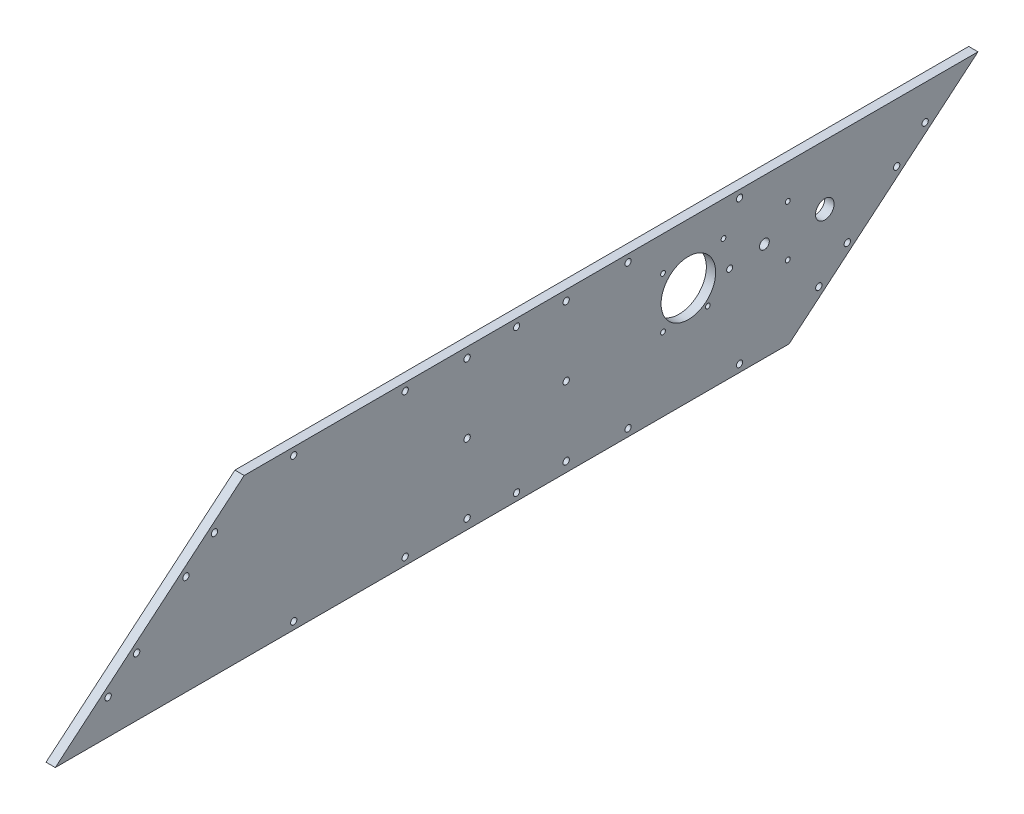
SolidWorks part; units mm, degrees
material "6061-T6 (SS)"
ref_plane "Front Plane" through (0, 0, 0) normal (0, 0, 1) x (1, 0, 0)
ref_plane "Top Plane" through (0, 0, 0) normal (0, 1, 0) x (1, 0, 0)
ref_plane "Right Plane" through (0, 0, 0) normal (1, 0, 0) x (0, 0, -1)
sketch "Sketch1" plane through (0, 0, 0) normal (1, 0, 0) x (0, 0, -1)
  line L0 (0, 12.7) -> (0, -12.7) construction
  line L1 (0, -12.7) -> (33.2976, -40.64) construction
  line L2 (33.2976, -40.64) -> (312.6976, -40.64)
  line L3 (312.6976, -40.64) -> (345.9952, -12.7)
  line L4 (345.9952, -12.7) -> (345.9952, 12.7) construction
  line L5 (345.9952, 12.7) -> (312.6976, 40.64) construction
  line L6 (312.6976, 40.64) -> (33.2976, 40.64)
  line L7 (33.2976, 40.64) -> (0, 12.7)
  line L8 (33.2976, 40.64) -> (33.2976, -40.64) construction
  line L9 (312.6976, 40.64) -> (312.6976, -40.64) construction
  line L10 (0, 0) -> (345.9952, 0) construction
  line L11 (0, 12.7) -> (-63.5681, -40.64)
  line L12 (-63.5681, -40.64) -> (33.2976, -40.64)
  line L13 (312.6976, 40.64) -> (409.5633, 40.64)
  line L14 (409.5633, 40.64) -> (345.9952, -12.7)
  point P10 (33.2976, 0)
  point P12 (312.6976, 0)
  dimension "D1" = 81.28
  dimension "D2" = 279.4
  dimension "D3" = 25.4
  dimension "D4" = 40
extrude "Boss-Extrude1" add sketch "Sketch1" along normal blind 4.7625
sketch "Sketch2" plane through (4.7625, 0, 0) normal (1, 0, 0) x (0, 0, -1)
  line L0 (-3.2177, 10) -> (373.048, 10) construction
  line L1 (312.6976, -40.64) -> (409.5633, 40.64) construction
  line L2 (345.048, 10) -> (245.048, 10) construction
  line L3 (245.048, -5) -> (345.048, -5) construction
  line L4 (245.048, -5) -> (245.048, 25) construction
  line L5 (245.048, 25) -> (345.048, 25) construction
  line L6 (345.048, -5) -> (345.048, 25) construction
  line L7 (33.2976, 40.64) -> (-63.5681, -40.64) construction
  line L9 (0, 0) -> (361.1305, 0) construction
  circle A0 centre (300.048, 10) radius 2.5
  circle A1 centre (282.2147, 8) radius 1.51
  circle A2 centre (270.2178, 15.9334) radius 1.01 construction
  circle A3 centre (282.2147, 8) radius 11.4777 construction
  circle A4 centre (270.2178, 15.9334) radius 7.1501 construction
  circle A5 centre (300.048, 10) radius 12.827 construction
  circle A6 centre (261.048, 10) radius 14
  circle A7 centre (282.2147, 8) radius 5.1181 construction
  circle A8 centre (331.0042, 10) radius 4.7625
  point P11 (300.048, 10)
  point P12 (282.2147, 8)
  point P13 (270.2178, 15.9334)
  point P23 (261.048, 10)
  dimension "D5" = 5
  dimension "D6" = 3.02
  dimension "D7" = 2.02
  dimension "D8" = 25.654
  dimension "D9" = 22.9553
  dimension "D10" = 14.3002
  dimension "D12" = 28
  dimension "D13" = 10.2362
  dimension "D17" = 9.525
  dimension "D1" = 17.9451
  dimension "D2" = 14.3828
  dimension "D3" = 30
  dimension "D4" = 100
  dimension "D11" = 10.922
  dimension "D14" = 16
  dimension "D15" = 13
  dimension "D16" = 55
  dimension "D18" = 30.9562
  dimension "D19" = 28
  dimension "D20" = 10
extrude "Gearbox (with Slip fits)" cut sketch "Sketch2" against normal through all
hole_wizard "#4-40 Tapped Hole1" [suppressed] positions "Sketch4" profile "Sketch3" tap size "#4-40" standard "ANSI Inch"
sketch "Sketch4" plane through (0, 40.64, 0) normal (0, 1, 0) x (1, 0, 0)
  line L0 (2.3812, 312.6976) -> (2.3813, 33.2976) construction
  line L1 (4.7625, 312.6976) -> (0, 312.6976) construction
  line L2 (4.7625, 33.2976) -> (0, 33.2976) construction
  point P9 (2.3812, 306.3476)
  point P33 (2.3813, 260.1196)
  point P34 (2.3813, 213.8916)
  point P35 (2.3813, 167.6636)
  point P36 (2.3813, 121.4356)
  point P37 (2.3813, 75.2076)
  point P38 (2.3813, 28.9796)
  dimension "D1" = 6.35
sketch "Sketch3" plane through (2.3812, 40.64, -306.3476) normal (1, 0, 0) x (0, 0, 1)
  line L0 (0, 0) -> (0, 8.2992)
  line L1 (0, 8.2992) -> (1.1303, 7.62)
  line L2 (1.1303, 7.62) -> (1.1303, 0)
  line L5 (1.1303, 0) -> (0, 0)
  line L10 (0, 8.2992) -> (-1.1303, 7.62) construction
  line L11 (0, -6.35) -> (0, 107.95) construction
  dimension "Tap Drill Dia." = 2.2606
  dimension "Tap Drill Depth" = 7.62
  dimension "Drill Angle" = 118
cosmetic thread "Hole Thread1" [suppressed] parameters "D1"=5.588, "D2"=2.8448
cosmetic thread "Hole Thread2" [suppressed] parameters "D1"=5.588, "D2"=2.8448
cosmetic thread "Hole Thread3" [suppressed] parameters "D1"=5.588, "D2"=2.8448
cosmetic thread "Hole Thread4" [suppressed] parameters "D1"=5.588, "D2"=2.8448
cosmetic thread "Hole Thread5" [suppressed] parameters "D1"=5.588, "D2"=2.8448
cosmetic thread "Hole Thread6" [suppressed] parameters "D1"=5.588, "D2"=2.8448
cosmetic thread "Hole Thread7" [suppressed] parameters "D1"=5.588, "D2"=2.8448
sketch "Sketch5" plane through (4.7625, 0, 0) normal (1, 0, 0) x (0, 0, -1)
  line L0 (0, 0) -> (361.1305, 0) construction
  line L1 (28.757, 36.83) -> (405.0227, 36.83) construction
  line L4 (33.2976, 40.64) -> (-63.5681, -40.64) construction
  line L5 (409.5633, 40.64) -> (33.2976, 40.64) construction
  line L6 (312.6976, -40.64) -> (409.5633, 40.64) construction
  circle A0 centre (287.2976, 36.83) radius 1.5939
  circle A1 centre (230.1476, 36.83) radius 1.5939
  circle A2 centre (172.9976, 36.83) radius 1.5939
  circle A3 centre (115.8476, 36.83) radius 1.5938
  circle A4 centre (58.6976, 36.83) radius 1.5938
  circle A5 centre (58.6976, -36.83) radius 1.5938
  circle A6 centre (115.8476, -36.83) radius 1.5938
  circle A7 centre (172.9976, -36.83) radius 1.5939
  circle A8 centre (230.1476, -36.83) radius 1.5939
  circle A9 centre (287.2976, -36.83) radius 1.5939
  dimension "D1" = 3.1877
  dimension "D3" = 25.4
  dimension "D4" = 3.81
  dimension "D2" = 5
extrude "Cut-Extrude1" cut sketch "Sketch5" against normal through all
hole_wizard "#2 Clearance Hole1" positions "Sketch8" profile "Sketch7" hole size "#2" standard "ANSI Inch" end condition through all
sketch "Sketch8" plane through (4.7625, 0, 0) normal (1, 0, 0) x (0, 0, -1)
  line L0 (245.048, 40.64) -> (245.048, -40.64) construction
  line L1 (409.5633, 40.64) -> (33.2976, 40.64) construction
  line L2 (-63.5681, -40.64) -> (312.6976, -40.64) construction
  line L4 (245.048, -6) -> (291.9785, -6) construction
  line L7 (248.048, -6) -> (248.048, 23) construction
  line L8 (245.048, -3) -> (312.048, -3) construction
  line L10 (245.048, 23) -> (312.048, 23) construction
  line L11 (312.048, 23) -> (312.048, -3) construction
  circle A0 centre (261.048, 10) radius 14 construction
  point P17 (248.048, 23)
  point P19 (279.048, 23)
  point P21 (271.048, -3)
  point P31 (248.048, -3)
  point P41 (312.048, 23)
  point P43 (312.048, -3)
  dimension "D1" = 16
  dimension "D2" = 16
  dimension "D3" = 34
  dimension "D4" = 26
  dimension "D5" = 3
  dimension "D6" = 3
  dimension "D7" = 29
  dimension "D8" = 67
sketch "Sketch7" plane through (4.7625, 23, -248.048) normal (0, 1, 0) x (0, 0, -1)
  line L0 (0, 0) -> (0, 4.7625)
  line L1 (0, 4.7625) -> (1.2192, 4.7625)
  line L2 (1.2192, 4.7625) -> (1.2192, 0)
  line L5 (1.2192, 0) -> (0, 0)
  line L11 (0, -6.35) -> (0, 107.95) construction
  dimension "Thru Hole Dia." = 2.4384
  dimension "Thru Hole Depth" = 4.7625
hole_wizard "#4 Clearance Hole2" positions "Sketch10" profile "Sketch9" hole size "#4" standard "ANSI Inch" end condition through all
sketch "Sketch10" plane through (4.7625, 0, 0) normal (1, 0, 0) x (0, 0, -1)
  line L0 (-15.1353, 0) -> (361.1305, 0) construction
  line L1 (33.2976, 40.64) -> (-63.5681, -40.64) construction
  line L2 (312.6976, -40.64) -> (409.5633, 40.64) construction
  line L4 (27.2435, 35.56) -> (403.5092, 35.56) construction
  line L6 (409.5633, 40.64) -> (33.2976, 40.64) construction
  line L7 (147.5976, 35.56) -> (147.5976, -35.56) construction
  line L9 (198.3976, 35.56) -> (198.3976, -35.56) construction
  point P16 (147.5976, 35.56)
  point P18 (198.3976, 35.56)
  point P32 (198.3976, -35.56)
  point P33 (147.5976, -35.56)
  point P42 (147.5976, 0)
  point P44 (198.3976, 0)
  dimension "D1" = 5.08
  dimension "D2" = 114.3
  dimension "D3" = 165.1
sketch "Sketch9" plane through (4.7625, 35.56, -147.5976) normal (0, 1, 0) x (0, 0, -1)
  line L0 (0, 0) -> (0, 4.7625)
  line L1 (0, 4.7625) -> (1.6319, 4.7625)
  line L2 (1.6319, 4.7625) -> (1.6319, 0)
  line L5 (1.6319, 0) -> (0, 0)
  line L11 (0, -6.35) -> (0, 107.95) construction
  dimension "Thru Hole Dia." = 3.2639
  dimension "Thru Hole Depth" = 4.7625
hole_wizard "#4 Clearance Hole1" positions "Sketch12" profile "Sketch11" hole size "#4" standard "ANSI Inch"
sketch "Sketch12" plane through (4.7625, 0, 0) normal (1, 0, 0) x (0, 0, -1)
  line L9 (-15.1353, 0) -> (361.1305, 0) construction
  line L10 (33.2976, 40.64) -> (-63.5681, -40.64) construction
  line L11 (312.6976, -40.64) -> (409.5633, 40.64) construction
  line L13 (403.636, 40.64) -> (306.7703, -40.64) construction
  line L14 (409.5633, 40.64) -> (33.2976, 40.64) construction
  line L15 (-63.5681, -40.64) -> (312.6976, -40.64) construction
  line L17 (39.2249, 40.64) -> (-57.6408, -40.64) construction
  line L19 (-9.208, 0) -> (355.2032, 0) construction
  line L20 (-36.4485, -22.8575) -> (327.9626, -22.8575) construction
  line L22 (-21.8554, -10.6124) -> (342.5558, -10.6124) construction
  line L24 (3.4394, 10.6124) -> (367.8505, 10.6124) construction
  line L26 (18.0326, 22.8575) -> (382.4437, 22.8575) construction
  point P44 (327.9626, -22.8575)
  point P46 (342.5558, -10.6124)
  point P48 (367.8505, 10.6124)
  point P50 (382.4437, 22.8575)
  point P53 (-36.4485, -22.8575)
  point P55 (-21.8554, -10.6124)
  point P57 (3.4394, 10.6124)
  point P59 (18.0326, 22.8575)
  dimension "D1" = 19.05
  dimension "D2" = 16.51
  dimension "D3" = 16.51
  dimension "D4" = 19.05
  dimension "D5" = 3.81
  dimension "D6" = 3.81
sketch "Sketch11" plane through (4.7625, -22.8575, -327.9626) normal (0, 1, 0) x (0, 0, -1)
  line L0 (0, 0) -> (0, 5.8066)
  line L1 (0, 5.8066) -> (1.6319, 4.826)
  line L2 (1.6319, 4.826) -> (1.6319, 0)
  line L5 (1.6319, 0) -> (0, 0)
  line L10 (0, 5.8066) -> (-1.6319, 4.826) construction
  line L11 (0, -6.35) -> (0, 107.95) construction
  dimension "Hole Dia." = 3.2639
  dimension "Hole Depth" = 4.826
  dimension "Drill Angle" = 118
